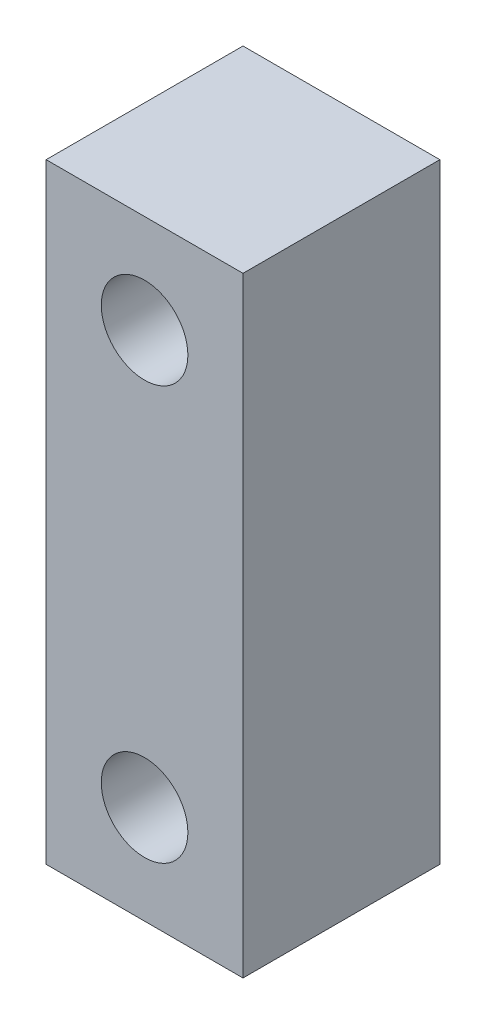
SolidWorks part; units mm, degrees
ref_plane "Front Plane" through (0, 0, 0) normal (0, 0, 1) x (1, 0, 0)
ref_plane "Top Plane" through (0, 0, 0) normal (0, 1, 0) x (1, 0, 0)
ref_plane "Right Plane" through (0, 0, 0) normal (1, 0, 0) x (0, 0, -1)
ref_plane "Plane1" through (0, 0, -25) normal (0, 0, -1) x (-1, 0, 0)
sketch "Sketch1" plane through (0, 0, -25) normal (0, 0, -1) x (-1, 0, 0)
  line L0 (5, 26) -> (-5, 26)
  line L1 (-5, 26) -> (-5, -5)
  line L2 (-5, -5) -> (5, -5)
  line L3 (5, -5) -> (5, 26)
  circle A0 centre (0, 0) radius 2.2
  circle A1 centre (0, 21) radius 2.2
extrude "Boss-Extrude1" add sketch "Sketch1" against normal blind 10
